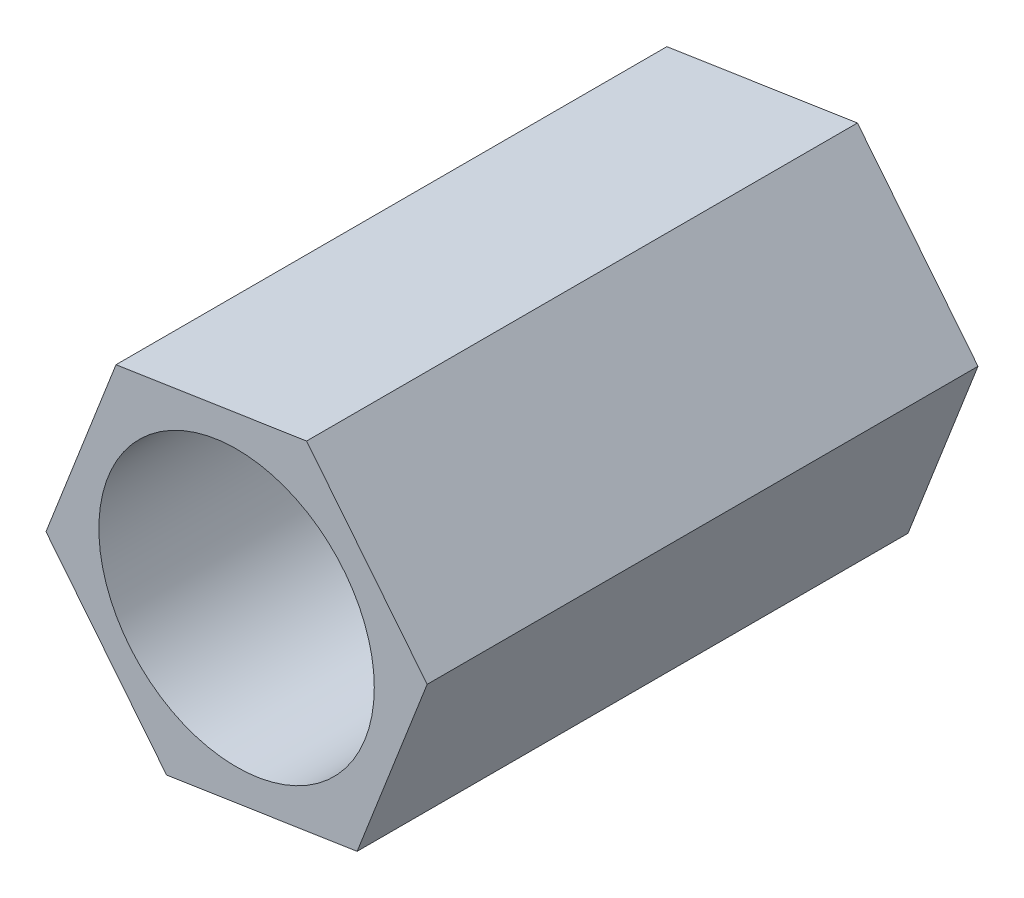
SolidWorks part; units mm, degrees
ref_plane "Front Plane" through (0, 0, 0) normal (0, 0, 1) x (1, 0, 0)
ref_plane "Top Plane" through (0, 0, 0) normal (0, 1, 0) x (1, 0, 0)
ref_plane "Right Plane" through (0, 0, 0) normal (1, 0, 0) x (0, 0, -1)
sketch "Sketch1" plane through (0, 0, 0) normal (0, 0, 1) x (1, 0, 0)
  circle A0 centre (0, 0) radius 1.25
  circle A1 centre (0, 0) radius 1.75
  dimension "D1" = 2.5
  dimension "D2" = 3.5
extrude "Boss-Extrude1" add sketch "Sketch1" along normal blind 5
sketch "Sketch2" plane through (0, 0, 5) normal (0, 0, 1) x (1, 0, 0)
  line L1 (1.0943, -1.3656) -> (1.7298, 0.2649)
  line L2 (1.7298, 0.2649) -> (0.6355, 1.6305)
  line L3 (0.6355, 1.6305) -> (-1.0943, 1.3656)
  line L4 (-1.0943, 1.3656) -> (-1.7298, -0.2649)
  line L5 (-1.7298, -0.2649) -> (-0.6355, -1.6305)
  line L6 (-0.6355, -1.6305) -> (1.0943, -1.3656)
  circle A0 centre (0, 0) radius 1.5155 construction
  circle M7 centre (0, 0) radius 1.75
  dimension "D1" = 1.75
extrude "Cut-Extrude2" cut sketch "Sketch2" against normal blind 12 contours L4 M7 | L3 M7 | L2 M7 | L1 M7 | L6 M7 | L5 M7
